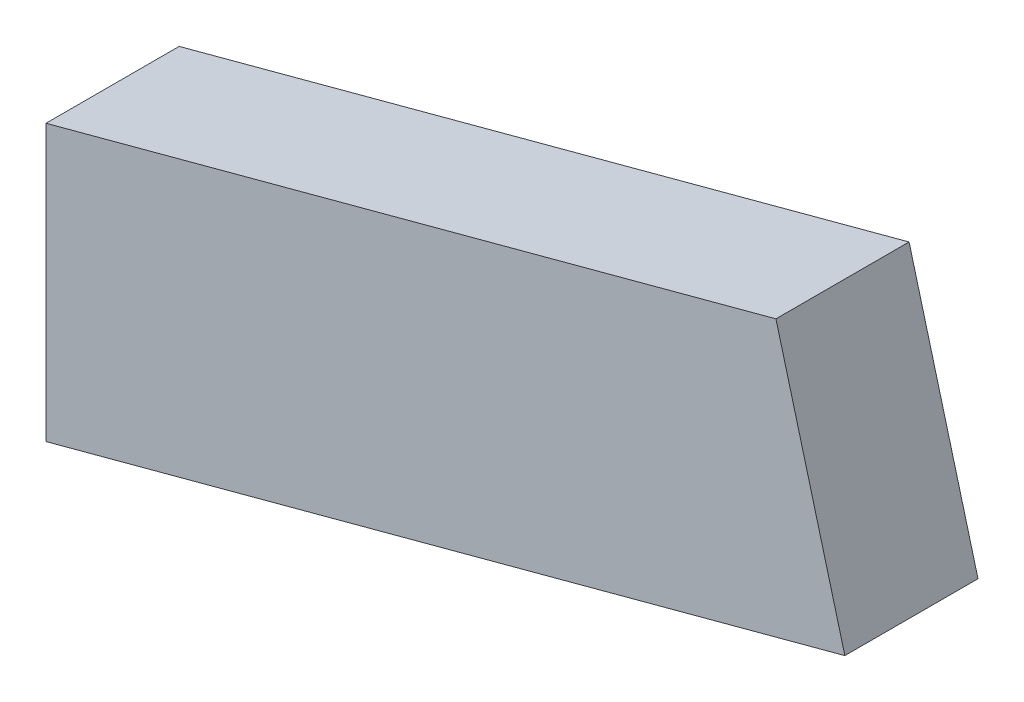
SolidWorks part; units mm, degrees
ref_plane "Front Plane" through (0, 0, 0) normal (0, 0, 1) x (1, 0, 0)
ref_plane "Top Plane" through (0, 0, 0) normal (0, 1, 0) x (1, 0, 0)
ref_plane "Right Plane" through (0, 0, 0) normal (1, 0, 0) x (0, 0, -1)
sketch "Sketch2" plane through (0, 0, 0) normal (0, 0, 1) x (1, 0, 0)
  line L4 (0, 0) -> (0, 1.0353)
  line L5 (0, 0) -> (3, 0.8038)
  line L6 (3, 0.8038) -> (2.7412, 1.7698)
  line L7 (2.7412, 1.7698) -> (0, 1.0353)
  point P5 (0, 0)
  dimension "D1" = 3
  dimension "D2" = 1
  dimension "D3" = 75
extrude "Boss-Extrude1" add sketch "Sketch2" along normal blind 0.5
